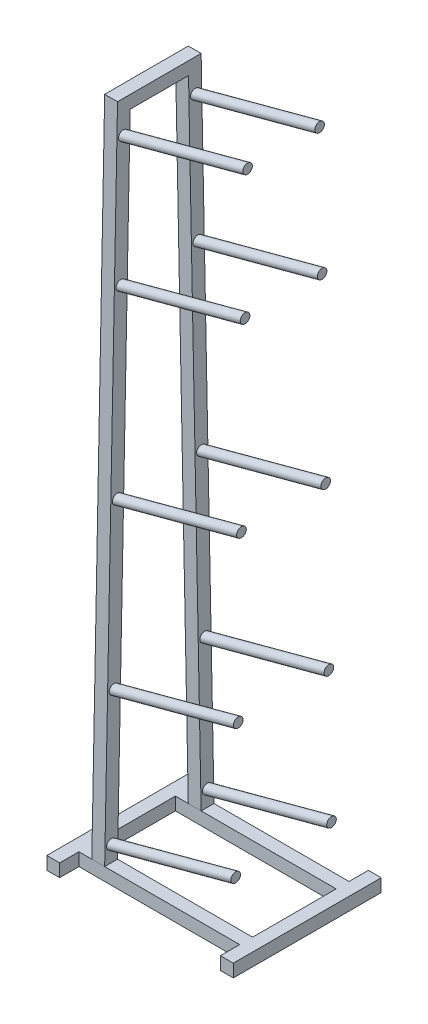
SolidWorks part; units mm, degrees
ref_plane "Front Plane" through (0, 0, 0) normal (0, 0, 1) x (1, 0, 0)
ref_plane "Top Plane" through (0, 0, 0) normal (0, 1, 0) x (1, 0, 0)
ref_plane "Right Plane" through (0, 0, 0) normal (1, 0, 0) x (0, 0, -1)
sketch "Sketch1" plane through (0, 0, 0) normal (0, 0, 1) x (1, 0, 0)
  line L1 (0, 0) -> (25.4, 0)
  line L2 (0, 0) -> (0, 25.4)
  line L3 (0, 25.4) -> (25.4, 25.4)
  line L4 (25.4, 0) -> (25.4, 25.4)
  dimension "D1" = 25.4
  dimension "D2" = 25.4
extrude "Boss-Extrude1" add sketch "Sketch1" along normal blind 292.1
sketch "Sketch2" plane through (25.4, 0, 0) normal (1, 0, 0) x (0, 0, -1)
  line L0 (-292.1, 25.4) -> (0, 25.4) construction
  line L1 (-254, 25.4) -> (-228.6, 25.4)
  line L2 (-254, 25.4) -> (-254, 0)
  line L3 (-254, 0) -> (-228.6, 0)
  line L4 (-228.6, 25.4) -> (-228.6, 0)
  line L5 (-292.1, 0) -> (0, 0) construction
  line L6 (-292.1, 25.4) -> (-254, 25.4) construction
  line L7 (-63.5, 25.4) -> (-38.1, 25.4)
  line L8 (-63.5, 25.4) -> (-63.5, 0)
  line L9 (-63.5, 0) -> (-38.1, 0)
  line L10 (-38.1, 25.4) -> (-38.1, 0)
  line L11 (-38.1, 25.4) -> (0, 25.4) construction
  dimension "D1" = 25.4
  dimension "D2" = 25.4
  dimension "D3" = 165.1
extrude "Boss-Extrude2" add sketch "Sketch2" along normal blind 317.5
ref_plane "Plane1" through (184.15, 0, 0) normal (1, 0, 0) x (0, 0, -1)
mirror "Mirror1" about plane through (184.15, 0, 0) normal (1, 0, 0) of "Boss-Extrude1"
ref_plane "Plane2" through (50.8, 0, 0) normal (-1, 0, 0) x (0, 0, 1)
sketch "Sketch3" plane through (50.8, 0, 0) normal (-1, 0, 0) x (0, 0, 1)
  line L0 (38.1, 25.4) -> (63.5, 1320.8)
  line L1 (254, 25.4) -> (228.6, 1320.8)
  line L2 (292.1, 0) -> (0, 0) construction
  line L3 (63.5, 1320.8) -> (0, 1320.8) construction
  line L4 (228.6, 1320.8) -> (292.1, 1320.8) construction
  line L5 (63.5049, 25.4) -> (88.4068, 1295.4)
  line L6 (292.1, 25.4) -> (0, 25.4) construction
  line L7 (228.5951, 25.4) -> (203.6932, 1295.4)
  line L8 (63.5, 1320.8) -> (88.9049, 1320.8)
  line L9 (203.1951, 1320.8) -> (228.6, 1320.8)
  line L10 (38.1, 25.4) -> (63.5049, 25.4)
  line L11 (228.5951, 25.4) -> (254, 25.4)
  line L12 (88.9049, 1320.8) -> (203.1951, 1320.8)
  line L13 (203.6932, 1295.4) -> (88.4068, 1295.4)
  dimension "D1" = 1320.8
  dimension "D2" = 165.1
  dimension "D3" = 25.4
  dimension "D4" = 25.4
  dimension "D5" = 25.4
extrude "Boss-Extrude3" add sketch "Sketch3" against normal blind 25.4
ref_plane "Plane3" through (53.747, 14.4015, 0) normal (-0.9659, -0.2588, 0) x (0, 0, 1)
sketch "Sketch4" plane through (76.2, 0, 0) normal (1, 0, 0) x (0, 0, -1)
  line L0 (-241.3, 25.4) -> (-215.9, 1320.8) construction
  line L1 (-228.6, 25.4) -> (-254, 25.4) construction
  line L2 (-228.6, 1320.8) -> (-63.5, 1320.8) construction
  line L3 (-254, 25.4) -> (-228.6, 1320.8) construction
  circle A0 centre (-240.6745, 57.2982) radius 9.525
  circle A1 centre (-235.5308, 319.6279) radius 9.525
  circle A2 centre (-229.2107, 641.9566) radius 9.525
  circle A3 centre (-217.142, 1257.4572) radius 9.525
  circle A4 centre (-222.109, 1004.1413) radius 9.525
  point P18 (-224.5686, 641.9566)
  point P19 (-234.804, 1004.3965)
  point P20 (-240.6745, 319.6279)
  point P21 (0, 0)
  dimension "D1" = 19.05
extrude "Boss-Extrude5" add sketch "Sketch4" along direction (-0.9659, -0.2588, 0) on the side of the normal blind 254
sketch "Sketch5" plane through (76.2, 0, 0) normal (1, 0, 0) x (0, 0, -1)
  line L0 (-146.05, 1320.8) -> (-146.05, 1160.9126) construction
ref_plane "Plane4" through (0, 0, 146.05) normal (0, 0, 1) x (0, -1, 0)
mirror "Mirror2" about plane through (0, 0, 146.05) normal (0, 0, 1) of "Boss-Extrude5"
